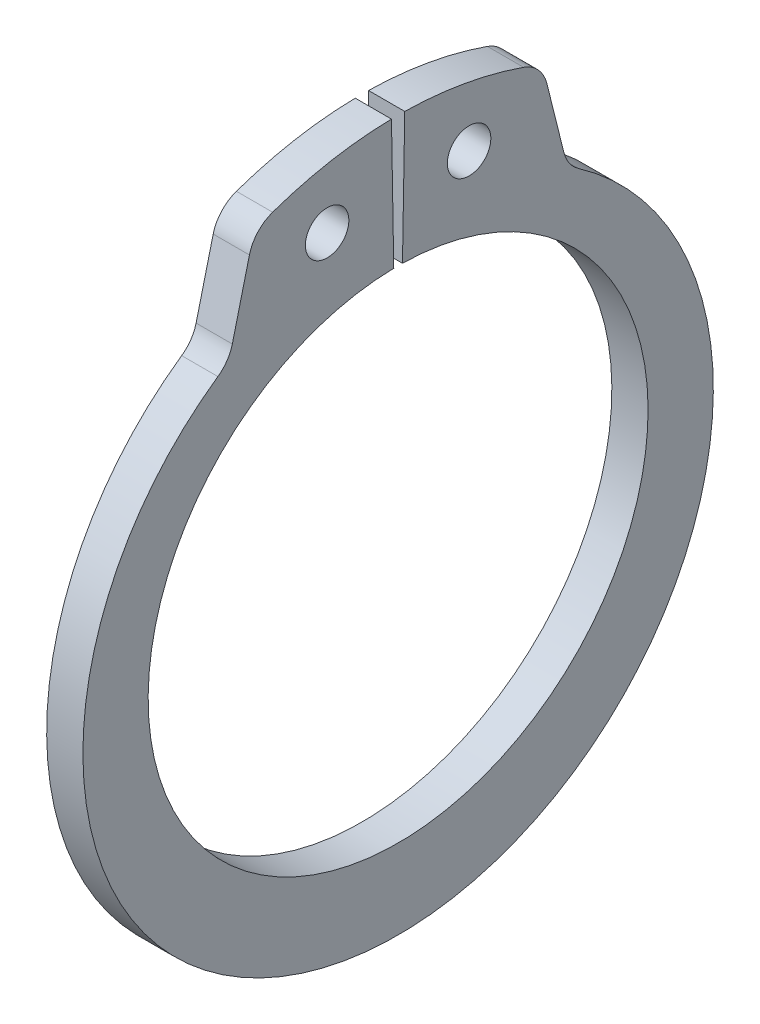
SolidWorks part; units mm, degrees
ref_plane "Front Plane" through (0, 0, 0) normal (0, 0, 1) x (1, 0, 0)
ref_plane "Top Plane" through (0, 0, 0) normal (0, 1, 0) x (1, 0, 0)
ref_plane "Right Plane" through (0, 0, 0) normal (1, 0, 0) x (0, 0, -1)
ref_plane "Plane1" through (-0.5, 0, 0) normal (-1, 0, 0) x (0, -1, 0)
sketch "Sketch1" plane through (-0.5, 0, 0) normal (-1, 0, 0) x (0, -1, 0)
  line L0 (-10.4984, 0.1833) -> (-6.8989, 0.1204)
  line L1 (-6.8989, -0.1204) -> (-10.4984, -0.1833)
  line L2 (-9.2101, -4.1043) -> (-7.3176, -4.5762)
  line L3 (-7.3176, 4.5762) -> (-9.2101, 4.1043)
  circle A0 centre (-8.6671, -1.9596) radius 0.6
  arc A1 (-9.2101, 4.1043) -> (-9.9122, 3.4639) centre (-8.9682, 3.134) ccw
  arc A2 (-9.9122, 3.4639) -> (-10.4984, 0.1833) centre (0, 0) ccw
  arc A3 (-6.8989, 0.1204) -> (-6.8989, -0.1204) centre (0, 0) cw
  arc A4 (-10.4984, -0.1833) -> (-9.9122, -3.4639) centre (0, 0) ccw
  arc A5 (-9.9122, -3.4639) -> (-9.2101, -4.1043) centre (-8.9682, -3.134) ccw
  arc A6 (-7.3176, -4.5762) -> (-6.7391, -4.9747) centre (-7.5595, -5.5465) cw
  arc A7 (-6.7391, -4.9747) -> (-6.7391, 4.9747) centre (0.3992, 0) ccw
  arc A8 (-6.7391, 4.9747) -> (-7.3176, 4.5762) centre (-7.5595, 5.5465) cw
  circle A9 centre (-8.6671, 1.9596) radius 0.6
extrude "Boss-Extrude1" add sketch "Sketch1" against normal blind 1
